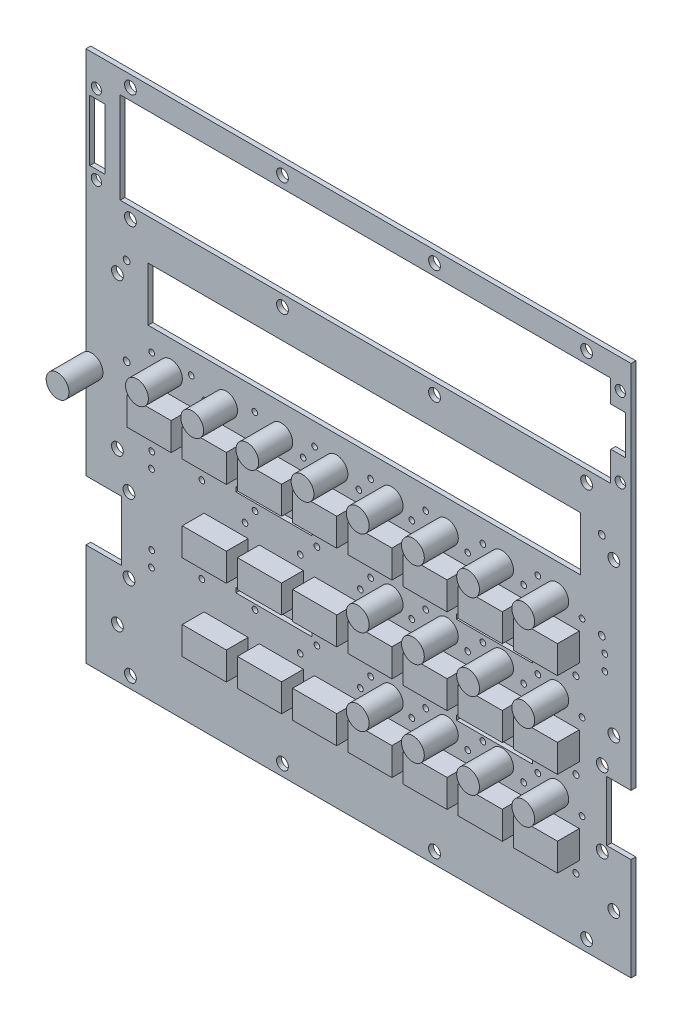
SolidWorks part; units mm, degrees
ref_plane "Front Plane" through (0, 0, 0) normal (0, 0, 1) x (1, 0, 0)
ref_plane "Top Plane" through (0, 0, 0) normal (0, 1, 0) x (1, 0, 0)
ref_plane "Right Plane" through (0, 0, 0) normal (1, 0, 0) x (0, 0, -1)
sketch "Sketch1" plane through (0, 0, 0) normal (0, 0, 1) x (1, 0, 0)
  line L0 (0, 0) -> (182.118, 0)
  line L1 (182.118, 0) -> (182.118, 34.2468)
  line L2 (182.118, 34.2468) -> (173.9875, 34.2468)
  line L3 (173.9875, 34.2468) -> (173.9875, 54.2468)
  line L4 (173.9875, 54.2468) -> (182.118, 54.2468)
  line L5 (182.118, 54.2468) -> (182.118, 177.8)
  line L6 (182.118, 177.8) -> (0, 177.8)
  line L7 (0, 177.8) -> (0, 54.2468)
  line L8 (0, 54.2468) -> (11.8694, 54.2468)
  line L9 (11.8694, 54.2468) -> (11.8694, 34.2468)
  line L10 (11.8694, 34.2468) -> (0, 34.2468)
  line L11 (0, 34.2468) -> (0, 0)
  line L12 (20.7391, 108.1786) -> (20.7391, 126.1796)
  line L13 (20.7391, 126.1796) -> (165.3007, 126.1796)
  line L14 (165.3007, 126.1796) -> (165.3007, 108.1786)
  line L15 (165.3007, 108.1786) -> (20.7391, 108.1786)
  line L16 (1.27, 144.653) -> (1.27, 164.973)
  line L17 (1.27, 164.973) -> (6.35, 164.973)
  line L18 (6.35, 164.973) -> (6.35, 144.653)
  line L19 (6.35, 144.653) -> (1.27, 144.653)
  line L20 (12.7, 170.18) -> (175.26, 170.18)
  line L21 (175.26, 170.18) -> (175.26, 162.6616)
  line L22 (175.26, 162.6616) -> (180.086, 162.6616)
  line L23 (180.086, 162.6616) -> (180.2892, 162.4584)
  line L24 (180.2892, 162.4584) -> (180.2892, 149.606)
  line L25 (180.2892, 149.606) -> (175.3616, 149.606)
  line L26 (175.3616, 149.606) -> (175.26, 149.5044)
  line L27 (175.26, 149.5044) -> (175.26, 139.7)
  line L28 (175.26, 139.7) -> (12.7, 139.7)
  line L29 (12.7, 139.7) -> (11.43, 139.7)
  line L30 (11.43, 139.7) -> (11.43, 170.18)
  line L31 (11.43, 170.18) -> (12.7, 170.18)
  line L32 (50.0634, 45.4152) -> (50.0634, 47.0027)
  line L33 (50.0634, 47.0027) -> (75.4634, 47.0027)
  line L34 (75.4634, 47.0027) -> (75.4634, 45.4152)
  line L35 (75.4634, 45.4152) -> (50.0634, 45.4152)
  line L36 (123.8134, 45.4152) -> (123.8134, 47.0027)
  line L37 (123.8134, 47.0027) -> (149.2134, 47.0027)
  line L38 (149.2134, 47.0027) -> (149.2134, 45.4152)
  line L39 (149.2134, 45.4152) -> (123.8134, 45.4152)
  line L40 (123.8134, 74.6252) -> (123.8134, 76.2127)
  line L41 (123.8134, 76.2127) -> (149.2134, 76.2127)
  line L42 (149.2134, 76.2127) -> (149.2134, 74.6252)
  line L43 (149.2134, 74.6252) -> (123.8134, 74.6252)
  line L44 (50.0634, 74.6252) -> (50.0634, 76.2127)
  line L45 (50.0634, 76.2127) -> (75.4634, 76.2127)
  line L46 (75.4634, 76.2127) -> (75.4634, 74.6252)
  line L47 (75.4634, 74.6252) -> (50.0634, 74.6252)
extrude "BOARD" add sketch "Sketch1" along normal blind 1.5921 separate body
ref_plane "Plane1" through (0, 0, 1.5921) normal (0, 0, 1) x (1, 0, 0)
sketch "Sketch2" plane through (0, 0, 1.5921) normal (0, 0, 1) x (1, 0, 0)
  circle A0 centre (1.8694, 86.9188) radius 3.81
extrude "LED-KINGBRIGHT_3P_2P54-1" add sketch "Sketch2" along normal blind 11.3538 separate body
sketch "Sketch3" plane through (0, 0, 1.5921) normal (0, 0, 1) x (1, 0, 0)
  circle A0 centre (157.4597, 41.1988) radius 3.81
extrude "LED-KINGBRIGHT_3P_2P54-2" add sketch "Sketch3" along normal blind 11.3538 separate body
sketch "Sketch4" plane through (0, 0, 1.5921) normal (0, 0, 1) x (1, 0, 0)
  circle A0 centre (139.0222, 41.1988) radius 3.81
extrude "LED-KINGBRIGHT_3P_2P54-3" add sketch "Sketch4" along normal blind 11.3538 separate body
sketch "Sketch5" plane through (0, 0, 1.5921) normal (0, 0, 1) x (1, 0, 0)
  circle A0 centre (120.5847, 41.1988) radius 3.81
extrude "LED-KINGBRIGHT_3P_2P54-4" add sketch "Sketch5" along normal blind 11.3538 separate body
sketch "Sketch6" plane through (0, 0, 1.5921) normal (0, 0, 1) x (1, 0, 0)
  circle A0 centre (102.1472, 41.1988) radius 3.81
extrude "LED-KINGBRIGHT_3P_2P54-5" add sketch "Sketch6" along normal blind 11.3538 separate body
sketch "Sketch7" plane through (0, 0, 1.5921) normal (0, 0, 1) x (1, 0, 0)
  circle A0 centre (157.4597, 69.7738) radius 3.81
extrude "LED-KINGBRIGHT_3P_2P54-6" add sketch "Sketch7" along normal blind 11.3538 separate body
sketch "Sketch8" plane through (0, 0, 1.5921) normal (0, 0, 1) x (1, 0, 0)
  circle A0 centre (139.0222, 69.7738) radius 3.81
extrude "LED-KINGBRIGHT_3P_2P54-7" add sketch "Sketch8" along normal blind 11.3538 separate body
sketch "Sketch9" plane through (0, 0, 1.5921) normal (0, 0, 1) x (1, 0, 0)
  circle A0 centre (120.5847, 69.7738) radius 3.81
extrude "LED-KINGBRIGHT_3P_2P54-8" add sketch "Sketch9" along normal blind 11.3538 separate body
sketch "Sketch10" plane through (0, 0, 1.5921) normal (0, 0, 1) x (1, 0, 0)
  circle A0 centre (102.1472, 69.7738) radius 3.81
extrude "LED-KINGBRIGHT_3P_2P54-9" add sketch "Sketch10" along normal blind 11.3538 separate body
sketch "Sketch19" plane through (0, 0, 1.5921) normal (0, 0, 1) x (1, 0, 0)
  circle A0 centre (157.4597, 98.3488) radius 3.81
extrude "LED-KINGBRIGHT_3P_2P54-18" add sketch "Sketch19" along normal blind 11.3538 separate body
sketch "Sketch20" plane through (0, 0, 1.5921) normal (0, 0, 1) x (1, 0, 0)
  circle A0 centre (139.0222, 98.3488) radius 3.81
extrude "LED-KINGBRIGHT_3P_2P54-19" add sketch "Sketch20" along normal blind 11.3538 separate body
sketch "Sketch21" plane through (0, 0, 1.5921) normal (0, 0, 1) x (1, 0, 0)
  circle A0 centre (120.5847, 98.3488) radius 3.81
extrude "LED-KINGBRIGHT_3P_2P54-20" add sketch "Sketch21" along normal blind 11.3538 separate body
sketch "Sketch22" plane through (0, 0, 1.5921) normal (0, 0, 1) x (1, 0, 0)
  circle A0 centre (102.1472, 98.3488) radius 3.81
extrude "LED-KINGBRIGHT_3P_2P54-21" add sketch "Sketch22" along normal blind 11.3538 separate body
sketch "Sketch23" plane through (0, 0, 1.5921) normal (0, 0, 1) x (1, 0, 0)
  circle A0 centre (83.7097, 98.3488) radius 3.81
extrude "LED-KINGBRIGHT_3P_2P54-22" add sketch "Sketch23" along normal blind 11.3538 separate body
sketch "Sketch24" plane through (0, 0, 1.5921) normal (0, 0, 1) x (1, 0, 0)
  circle A0 centre (65.2722, 98.3488) radius 3.81
extrude "LED-KINGBRIGHT_3P_2P54-23" add sketch "Sketch24" along normal blind 11.3538 separate body
sketch "Sketch25" plane through (0, 0, 1.5921) normal (0, 0, 1) x (1, 0, 0)
  circle A0 centre (46.8347, 98.3488) radius 3.81
extrude "LED-KINGBRIGHT_3P_2P54-24" add sketch "Sketch25" along normal blind 11.3538 separate body
sketch "Sketch26" plane through (0, 0, 1.5921) normal (0, 0, 1) x (1, 0, 0)
  circle A0 centre (28.3972, 98.3488) radius 3.81
extrude "LED-KINGBRIGHT_3P_2P54-25" add sketch "Sketch26" along normal blind 11.3538 separate body
sketch "Sketch27" plane through (0, 0, 1.5921) normal (0, 0, 1) x (1, 0, 0)
  line L0 (150.0937, 25.3238) -> (150.0937, 34.5948)
  line L1 (150.0937, 34.5948) -> (164.8257, 34.5948)
  line L2 (164.8257, 34.5948) -> (164.8257, 25.3238)
  line L3 (164.8257, 25.3238) -> (150.0937, 25.3238)
extrude "SWITCH-MCDTS2-1" add sketch "Sketch27" along normal blind 7.3 separate body
sketch "Sketch28" plane through (0, 0, 1.5921) normal (0, 0, 1) x (1, 0, 0)
  line L0 (150.0937, 53.8988) -> (150.0937, 63.1698)
  line L1 (150.0937, 63.1698) -> (164.8257, 63.1698)
  line L2 (164.8257, 63.1698) -> (164.8257, 53.8988)
  line L3 (164.8257, 53.8988) -> (150.0937, 53.8988)
extrude "SWITCH-MCDTS2-2" add sketch "Sketch28" along normal blind 7.3 separate body
sketch "Sketch29" plane through (0, 0, 1.5921) normal (0, 0, 1) x (1, 0, 0)
  line L0 (131.6562, 25.3238) -> (131.6562, 34.5948)
  line L1 (131.6562, 34.5948) -> (146.3882, 34.5948)
  line L2 (146.3882, 34.5948) -> (146.3882, 25.3238)
  line L3 (146.3882, 25.3238) -> (131.6562, 25.3238)
extrude "SWITCH-MCDTS2-3" add sketch "Sketch29" along normal blind 7.3 separate body
sketch "Sketch30" plane through (0, 0, 1.5921) normal (0, 0, 1) x (1, 0, 0)
  line L0 (113.2187, 25.3238) -> (113.2187, 34.5948)
  line L1 (113.2187, 34.5948) -> (127.9507, 34.5948)
  line L2 (127.9507, 34.5948) -> (127.9507, 25.3238)
  line L3 (127.9507, 25.3238) -> (113.2187, 25.3238)
extrude "SWITCH-MCDTS2-4" add sketch "Sketch30" along normal blind 7.3 separate body
sketch "Sketch31" plane through (0, 0, 1.5921) normal (0, 0, 1) x (1, 0, 0)
  line L0 (94.7812, 25.3238) -> (94.7812, 34.5948)
  line L1 (94.7812, 34.5948) -> (109.5132, 34.5948)
  line L2 (109.5132, 34.5948) -> (109.5132, 25.3238)
  line L3 (109.5132, 25.3238) -> (94.7812, 25.3238)
extrude "SWITCH-MCDTS2-5" add sketch "Sketch31" along normal blind 7.3 separate body
sketch "Sketch32" plane through (0, 0, 1.5921) normal (0, 0, 1) x (1, 0, 0)
  line L0 (76.3437, 25.3238) -> (76.3437, 34.5948)
  line L1 (76.3437, 34.5948) -> (91.0757, 34.5948)
  line L2 (91.0757, 34.5948) -> (91.0757, 25.3238)
  line L3 (91.0757, 25.3238) -> (76.3437, 25.3238)
extrude "SWITCH-MCDTS2-6" add sketch "Sketch32" along normal blind 7.3 separate body
sketch "Sketch33" plane through (0, 0, 1.5921) normal (0, 0, 1) x (1, 0, 0)
  line L0 (57.9062, 25.3238) -> (57.9062, 34.5948)
  line L1 (57.9062, 34.5948) -> (72.6382, 34.5948)
  line L2 (72.6382, 34.5948) -> (72.6382, 25.3238)
  line L3 (72.6382, 25.3238) -> (57.9062, 25.3238)
extrude "SWITCH-MCDTS2-7" add sketch "Sketch33" along normal blind 7.3 separate body
sketch "Sketch34" plane through (0, 0, 1.5921) normal (0, 0, 1) x (1, 0, 0)
  line L0 (39.4687, 25.3238) -> (39.4687, 34.5948)
  line L1 (39.4687, 34.5948) -> (54.2007, 34.5948)
  line L2 (54.2007, 34.5948) -> (54.2007, 25.3238)
  line L3 (54.2007, 25.3238) -> (39.4687, 25.3238)
extrude "SWITCH-MCDTS2-8" add sketch "Sketch34" along normal blind 7.3 separate body
sketch "Sketch36" plane through (0, 0, 1.5921) normal (0, 0, 1) x (1, 0, 0)
  line L0 (131.6562, 53.8988) -> (131.6562, 63.1698)
  line L1 (131.6562, 63.1698) -> (146.3882, 63.1698)
  line L2 (146.3882, 63.1698) -> (146.3882, 53.8988)
  line L3 (146.3882, 53.8988) -> (131.6562, 53.8988)
extrude "SWITCH-MCDTS2-10" add sketch "Sketch36" along normal blind 7.3 separate body
sketch "Sketch37" plane through (0, 0, 1.5921) normal (0, 0, 1) x (1, 0, 0)
  line L0 (113.2187, 53.8988) -> (113.2187, 63.1698)
  line L1 (113.2187, 63.1698) -> (127.9507, 63.1698)
  line L2 (127.9507, 63.1698) -> (127.9507, 53.8988)
  line L3 (127.9507, 53.8988) -> (113.2187, 53.8988)
extrude "SWITCH-MCDTS2-11" add sketch "Sketch37" along normal blind 7.3 separate body
sketch "Sketch38" plane through (0, 0, 1.5921) normal (0, 0, 1) x (1, 0, 0)
  line L0 (94.7812, 53.8988) -> (94.7812, 63.1698)
  line L1 (94.7812, 63.1698) -> (109.5132, 63.1698)
  line L2 (109.5132, 63.1698) -> (109.5132, 53.8988)
  line L3 (109.5132, 53.8988) -> (94.7812, 53.8988)
extrude "SWITCH-MCDTS2-12" add sketch "Sketch38" along normal blind 7.3 separate body
sketch "Sketch39" plane through (0, 0, 1.5921) normal (0, 0, 1) x (1, 0, 0)
  line L0 (76.3437, 53.8988) -> (76.3437, 63.1698)
  line L1 (76.3437, 63.1698) -> (91.0757, 63.1698)
  line L2 (91.0757, 63.1698) -> (91.0757, 53.8988)
  line L3 (91.0757, 53.8988) -> (76.3437, 53.8988)
extrude "SWITCH-MCDTS2-13" add sketch "Sketch39" along normal blind 7.3 separate body
sketch "Sketch40" plane through (0, 0, 1.5921) normal (0, 0, 1) x (1, 0, 0)
  line L0 (57.9062, 53.8988) -> (57.9062, 63.1698)
  line L1 (57.9062, 63.1698) -> (72.6382, 63.1698)
  line L2 (72.6382, 63.1698) -> (72.6382, 53.8988)
  line L3 (72.6382, 53.8988) -> (57.9062, 53.8988)
extrude "SWITCH-MCDTS2-14" add sketch "Sketch40" along normal blind 7.3 separate body
sketch "Sketch41" plane through (0, 0, 1.5921) normal (0, 0, 1) x (1, 0, 0)
  line L0 (39.4687, 53.8988) -> (39.4687, 63.1698)
  line L1 (39.4687, 63.1698) -> (54.2007, 63.1698)
  line L2 (54.2007, 63.1698) -> (54.2007, 53.8988)
  line L3 (54.2007, 53.8988) -> (39.4687, 53.8988)
extrude "SWITCH-MCDTS2-15" add sketch "Sketch41" along normal blind 7.3 separate body
sketch "Sketch43" plane through (0, 0, 1.5921) normal (0, 0, 1) x (1, 0, 0)
  line L0 (150.0937, 82.4738) -> (150.0937, 91.7448)
  line L1 (150.0937, 91.7448) -> (164.8257, 91.7448)
  line L2 (164.8257, 91.7448) -> (164.8257, 82.4738)
  line L3 (164.8257, 82.4738) -> (150.0937, 82.4738)
extrude "SWITCH-MCDTS2-17" add sketch "Sketch43" along normal blind 7.3 separate body
sketch "Sketch44" plane through (0, 0, 1.5921) normal (0, 0, 1) x (1, 0, 0)
  line L0 (131.6562, 82.4738) -> (131.6562, 91.7448)
  line L1 (131.6562, 91.7448) -> (146.3882, 91.7448)
  line L2 (146.3882, 91.7448) -> (146.3882, 82.4738)
  line L3 (146.3882, 82.4738) -> (131.6562, 82.4738)
extrude "SWITCH-MCDTS2-18" add sketch "Sketch44" along normal blind 7.3 separate body
sketch "Sketch45" plane through (0, 0, 1.5921) normal (0, 0, 1) x (1, 0, 0)
  line L0 (113.2187, 82.4738) -> (113.2187, 91.7448)
  line L1 (113.2187, 91.7448) -> (127.9507, 91.7448)
  line L2 (127.9507, 91.7448) -> (127.9507, 82.4738)
  line L3 (127.9507, 82.4738) -> (113.2187, 82.4738)
extrude "SWITCH-MCDTS2-19" add sketch "Sketch45" along normal blind 7.3 separate body
sketch "Sketch46" plane through (0, 0, 1.5921) normal (0, 0, 1) x (1, 0, 0)
  line L0 (94.7812, 82.4738) -> (94.7812, 91.7448)
  line L1 (94.7812, 91.7448) -> (109.5132, 91.7448)
  line L2 (109.5132, 91.7448) -> (109.5132, 82.4738)
  line L3 (109.5132, 82.4738) -> (94.7812, 82.4738)
extrude "SWITCH-MCDTS2-20" add sketch "Sketch46" along normal blind 7.3 separate body
sketch "Sketch47" plane through (0, 0, 1.5921) normal (0, 0, 1) x (1, 0, 0)
  line L0 (76.3437, 82.4738) -> (76.3437, 91.7448)
  line L1 (76.3437, 91.7448) -> (91.0757, 91.7448)
  line L2 (91.0757, 91.7448) -> (91.0757, 82.4738)
  line L3 (91.0757, 82.4738) -> (76.3437, 82.4738)
extrude "SWITCH-MCDTS2-21" add sketch "Sketch47" along normal blind 7.3 separate body
sketch "Sketch48" plane through (0, 0, 1.5921) normal (0, 0, 1) x (1, 0, 0)
  line L0 (57.9062, 82.4738) -> (57.9062, 91.7448)
  line L1 (57.9062, 91.7448) -> (72.6382, 91.7448)
  line L2 (72.6382, 91.7448) -> (72.6382, 82.4738)
  line L3 (72.6382, 82.4738) -> (57.9062, 82.4738)
extrude "SWITCH-MCDTS2-22" add sketch "Sketch48" along normal blind 7.3 separate body
sketch "Sketch49" plane through (0, 0, 1.5921) normal (0, 0, 1) x (1, 0, 0)
  line L0 (39.4687, 82.4738) -> (39.4687, 91.7448)
  line L1 (39.4687, 91.7448) -> (54.2007, 91.7448)
  line L2 (54.2007, 91.7448) -> (54.2007, 82.4738)
  line L3 (54.2007, 82.4738) -> (39.4687, 82.4738)
extrude "SWITCH-MCDTS2-23" add sketch "Sketch49" along normal blind 7.3 separate body
sketch "Sketch50" plane through (0, 0, 1.5921) normal (0, 0, 1) x (1, 0, 0)
  line L0 (21.0312, 82.4738) -> (21.0312, 91.7448)
  line L1 (21.0312, 91.7448) -> (35.7632, 91.7448)
  line L2 (35.7632, 91.7448) -> (35.7632, 82.4738)
  line L3 (35.7632, 82.4738) -> (21.0312, 82.4738)
extrude "SWITCH-MCDTS2-24" add sketch "Sketch50" along normal blind 7.3 separate body
sketch "Sketch56" plane through (0, 0, 1.5921) normal (0, 0, 1) x (1, 0, 0)
  circle B0 centre (163.703, 21.1074) radius 1.016
  circle B1 centre (163.703, 49.6824) radius 1.016
  circle B2 centre (145.2626, 21.8186) radius 0.9652
  circle B3 centre (126.8476, 21.6154) radius 0.9652
  circle B4 centre (108.4072, 21.7424) radius 0.9652
  circle B5 centre (89.9668, 21.844) radius 0.9652
  circle B6 centre (71.5264, 20.7772) radius 0.9652
  circle B7 centre (53.086, 21.1582) radius 0.9652
  circle B8 centre (34.6472, 21.1328) radius 1.016
  circle B9 centre (145.2626, 49.5554) radius 1.016
  circle B10 centre (126.8222, 49.3522) radius 1.016
  circle B11 centre (108.3818, 49.1236) radius 1.016
  circle B12 centre (89.9414, 49.6824) radius 1.016
  circle B13 centre (71.501, 49.1998) radius 1.016
  circle B14 centre (53.0606, 49.1998) radius 1.016
  circle B15 centre (34.6202, 49.276) radius 1.016
  circle B16 centre (163.703, 78.2574) radius 1.016
  circle B17 centre (145.2626, 77.7748) radius 1.016
  circle B18 centre (126.746, 78.3336) radius 1.016
  circle B19 centre (108.3818, 78.74) radius 1.016
  circle B20 centre (89.9414, 78.3336) radius 1.016
  circle B21 centre (71.501, 78.2574) radius 1.016
  circle B22 centre (53.0606, 78.4098) radius 1.016
  circle B23 centre (34.6202, 78.0542) radius 1.016
  circle B24 centre (91.694, 38.6588) radius 0.9525
  circle B25 centre (77.1652, 43.7388) radius 0.9525
  circle B26 centre (71.5772, 38.6588) radius 0.9525
  circle B27 centre (56.4896, 43.7388) radius 0.9525
  circle B28 centre (38.735, 43.7388) radius 0.9525
  circle B29 centre (21.8948, 38.6588) radius 0.9525
  circle B30 centre (21.971, 43.7388) radius 0.9525
  circle B31 centre (77.1652, 72.3138) radius 0.9525
  circle B32 centre (91.694, 67.2338) radius 0.9525
  circle B33 centre (71.5772, 67.2338) radius 0.9525
  circle B34 centre (56.4896, 72.3138) radius 0.9525
  circle B35 centre (53.1368, 67.2338) radius 0.9525
  circle B36 centre (38.735, 72.3138) radius 0.9525
  circle B37 centre (21.8948, 67.2338) radius 0.9525
  circle B38 centre (21.971, 72.3138) radius 0.9525
  circle B39 centre (165.735, 95.8088) radius 0.9525
  circle B40 centre (150.9776, 100.8888) radius 0.9525
  circle B41 centre (146.2278, 95.8088) radius 0.9525
  circle B42 centre (132.6134, 100.8888) radius 0.9525
  circle B43 centre (113.4872, 100.8888) radius 0.9525
  circle B44 centre (127.508, 95.8088) radius 0.9525
  circle B45 centre (108.8644, 95.8088) radius 0.9525
  circle B46 centre (95.0976, 100.8888) radius 0.9525
  circle B47 centre (91.186, 95.8088) radius 0.9525
  circle B48 centre (76.3778, 100.8888) radius 0.9525
  circle B49 centre (72.5424, 95.8088) radius 0.9525
  circle B50 centre (56.4134, 100.8888) radius 0.9525
  circle B51 centre (39.7256, 95.8088) radius 0.9525
  circle B52 centre (35.179, 100.8888) radius 0.9525
  circle B53 centre (24.2062, 95.8088) radius 0.9525
  circle B54 centre (21.971, 100.8888) radius 0.9525
  circle B55 centre (132.6134, 72.3138) radius 0.9525
  circle B56 centre (146.2278, 67.2338) radius 0.9525
  circle B57 centre (113.4872, 72.3138) radius 0.9525
  circle B58 centre (127.508, 67.2338) radius 0.9525
  circle B59 centre (95.0976, 72.3138) radius 0.9525
  circle B60 centre (108.8644, 67.2338) radius 0.9525
  circle B61 centre (150.9776, 43.7388) radius 0.9525
  circle B62 centre (132.6134, 43.7388) radius 0.9525
  circle B63 centre (113.4872, 43.7388) radius 0.9525
  circle B64 centre (95.0976, 43.7388) radius 0.9525
  circle B65 centre (108.8644, 38.6588) radius 0.9525
  circle B66 centre (150.9776, 72.3138) radius 0.9525
  circle B67 centre (165.735, 67.2338) radius 0.9525
  circle B68 centre (173.3296, 89.4588) radius 0.9525
  circle B69 centre (173.355, 84.3534) radius 0.9525
  circle B70 centre (176.3725, 118.11) radius 1.9685
  circle B71 centre (176.3725, 67.31) radius 1.9685
  circle B72 centre (176.3725, 16.51) radius 1.9685
  circle B73 centre (167.259, 135.89) radius 1.9685
  circle B74 centre (116.459, 135.89) radius 1.9685
  circle B75 centre (65.659, 135.89) radius 1.9685
  circle B76 centre (14.859, 135.89) radius 1.9685
  circle B77 centre (10.5105, 118.11) radius 1.9685
  circle B78 centre (10.5105, 67.31) radius 1.9685
  circle B79 centre (10.5105, 16.51) radius 1.9685
  circle B80 centre (165.735, 38.6588) radius 0.9525
  circle B81 centre (146.2278, 38.6588) radius 0.9525
  circle B82 centre (127.508, 38.6588) radius 0.9525
  circle B83 centre (14.859, 173.99) radius 1.9685
  circle B84 centre (65.659, 173.99) radius 1.9685
  circle B85 centre (116.459, 173.99) radius 1.9685
  circle B86 centre (167.259, 173.99) radius 1.9685
  circle B87 centre (167.259, 3.81) radius 1.9685
  circle B88 centre (116.459, 3.81) radius 1.9685
  circle B89 centre (65.659, 3.81) radius 1.9685
  circle B90 centre (14.859, 3.81) radius 1.9685
  circle B91 centre (172.5066, 56.7436) radius 1.9685
  circle B92 centre (172.5066, 31.75) radius 1.9685
  circle B93 centre (14.3688, 56.7436) radius 1.9685
  circle B94 centre (14.3688, 31.75) radius 1.9685
  circle B95 centre (172.3415, 123.3754) radius 1.1303
  circle B96 centre (172.3415, 94.1654) radius 1.1303
  circle B97 centre (13.5915, 94.1654) radius 1.1303
  circle B98 centre (13.5915, 123.3754) radius 1.1303
  circle B99 centre (178.5137, 141.5618) radius 1.7145
  circle B100 centre (178.5137, 168.0616) radius 1.7145
  circle B101 centre (3.5001, 168.0616) radius 1.7145
  circle B102 centre (3.5001, 141.5618) radius 1.7145
sketch_block_instance "Block-Model-1"
sketch_block "Block-Model"
extrude "Cut-Extrude1" cut sketch "Sketch56" against normal blind 10
